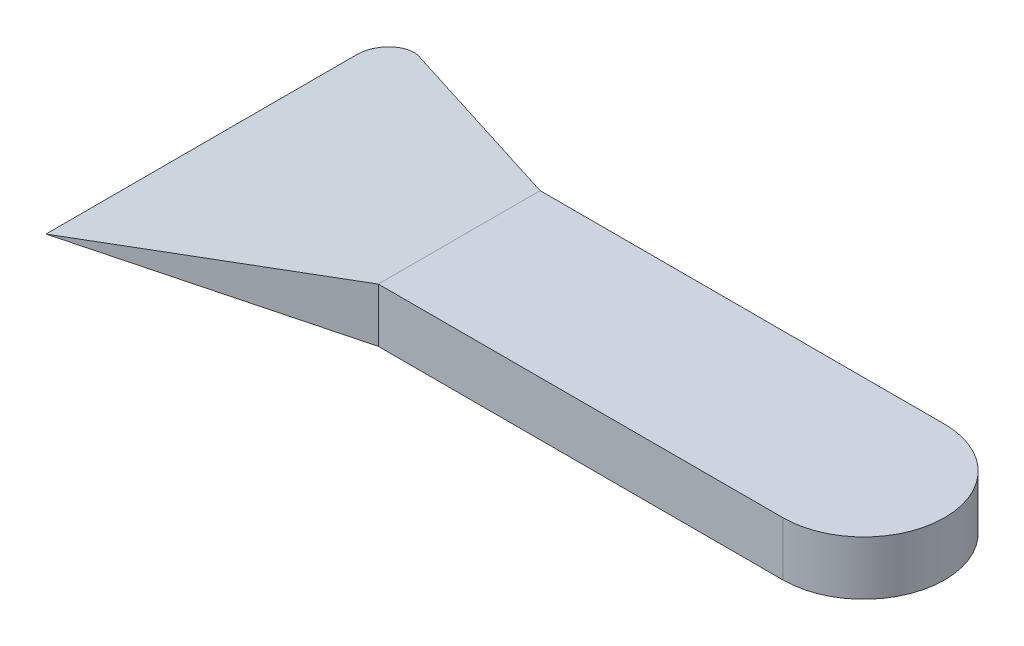
SolidWorks part; units mm, degrees
ref_plane "Front Plane" through (0, 0, 0) normal (0, 0, 1) x (1, 0, 0)
ref_plane "Top Plane" through (0, 0, 0) normal (0, 1, 0) x (1, 0, 0)
ref_plane "Right Plane" through (0, 0, 0) normal (1, 0, 0) x (0, 0, -1)
sketch "Sketch1" plane through (0, 0, 0) normal (0, 1, 0) x (1, 0, 0)
  line L0 (17.1829, 3) -> (17.1829, -3) construction
  line L3 (2.1829, 3) -> (-5.2177, 5.9094)
  line L4 (-6.5836, 4.9787) -> (-6.5836, -6.5536)
  line L5 (-6.5836, -6.5536) -> (2.1829, -3)
  line L6 (2.1829, 3) -> (17.1829, 3)
  line L8 (2.1829, -3) -> (17.1829, -3)
  line L9 (22.5745, 0) -> (-14.8462, 0) construction
  arc A2 (17.1829, -3) -> (17.1829, 3) centre (17.1829, 0) ccw
  arc A3 (-5.2177, 5.9094) -> (-6.5836, 4.9787) centre (-5.5836, 4.9787) ccw
  point P6 (-6.5836, 6.4464)
  dimension "D4" = 3
  dimension "D5" = 1
  dimension "D1" = 15
  dimension "D2" = 15
  dimension "D3" = 13
extrude "Boss-Extrude1" add sketch "Sketch1" along normal blind 2
ref_plane "Plane1" through (0, 0, 0) normal (0, 0, 1) x (1, 0, 0)
sketch "Sketch2" plane through (0, 0, 0) normal (0, 0, 1) x (1, 0, 0)
  line L0 (-7.3877, 1.0286) -> (20.7862, 1.0286) construction
  line L1 (-6.5836, 1) -> (2.1829, 2)
  line L2 (-6.5836, 2) -> (-6.5836, 0) construction
  line L3 (-6.5836, 1) -> (-6.5836, 2)
  line L4 (-6.5836, 2) -> (2.1829, 2)
extrude "Cut-Extrude1" cut sketch "Sketch2" against normal through all both and the other way through all
sketch "Sketch3" plane through (0, 0, 0) normal (0, 0, 1) x (1, 0, 0)
  line L0 (-6.5836, 1) -> (-6.5836, 0)
  line L1 (-6.5836, 1) -> (2.1829, 0)
  line L2 (2.1829, 0) -> (-6.5836, 0)
extrude "Cut-Extrude2" cut sketch "Sketch3" against normal through all both and the other way through all
